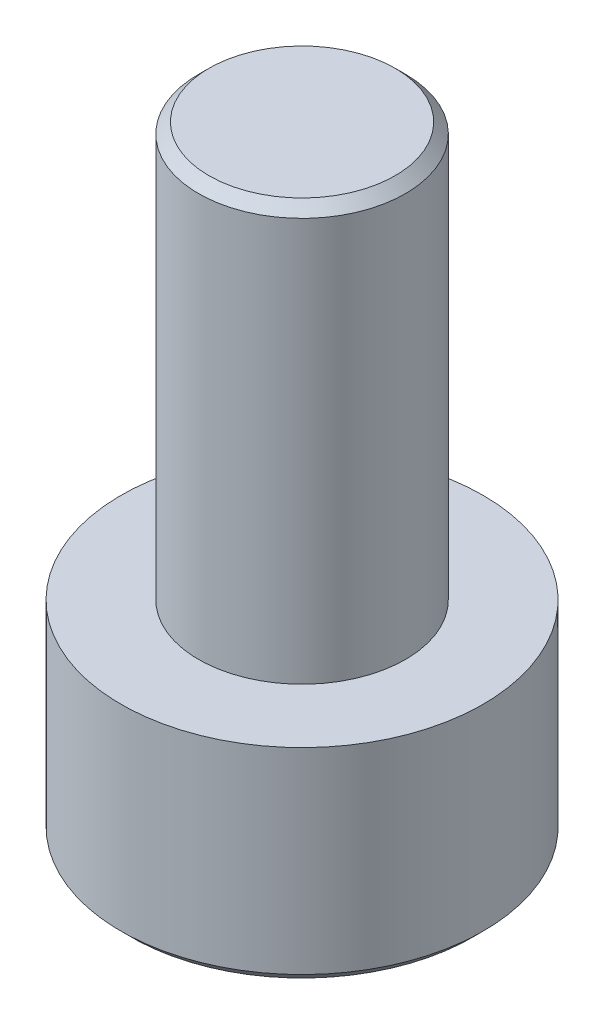
SolidWorks part; units mm, degrees
ref_plane "Front Plane" through (0, 0, 0) normal (0, 0, 1) x (1, 0, 0)
ref_plane "Top Plane" through (0, 0, 0) normal (0, 1, 0) x (1, 0, 0)
ref_plane "Right Plane" through (0, 0, 0) normal (1, 0, 0) x (0, 0, -1)
sketch "Reconstructed nominal axial profile" plane through (0, 0, 0) normal (0, 0, 1) x (1, 0, 0)
  line L0 (0, -500) -> (0, 50) construction
  line L1 (0, -4) -> (3.3, -4)
  line L2 (3.3, -4) -> (3.5, -3.8)
  line L3 (3.5, -3.8) -> (3.5, 0)
  line L4 (3.5, 0) -> (2, 0)
  line L5 (2, 0) -> (2, 7.8)
  line L6 (2, 7.8) -> (1.8, 8)
  line L7 (1.8, 8) -> (0, 8)
  line L8 (0, 8) -> (0, -4)
revolve "Native revolved geometry" add sketch "Reconstructed nominal axial profile" angle 360 about L0
sketch "Sketch2" plane through (0, 0, 0) normal (0, 1, 0) x (1, 0, 0)
  line L0 (1.7321, 0) -> (0.866, -1.5)
  line L1 (0.866, -1.5) -> (-0.866, -1.5)
  line L2 (-0.866, -1.5) -> (-1.7321, 0)
  line L3 (-1.7321, 0) -> (-0.866, 1.5)
  line L4 (-0.866, 1.5) -> (0.866, 1.5)
  line L5 (0.866, 1.5) -> (1.7321, 0)
extrude "Simplified nominal hex socket" cut sketch "Sketch2" along normal blind 2 from offset 4
